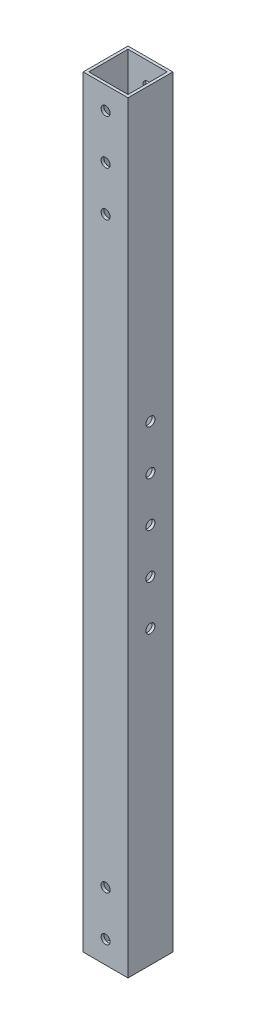
SolidWorks part; units mm, degrees
material "6061-T6 (SS)"
ref_plane "Front Plane" through (0, 0, 0) normal (0, 0, 1) x (1, 0, 0)
ref_plane "Top Plane" through (0, 0, 0) normal (0, 1, 0) x (1, 0, 0)
ref_plane "Right Plane" through (0, 0, 0) normal (1, 0, 0) x (0, 0, -1)
sketch "Sketch1" plane through (0, 0, 0) normal (0, 1, 0) x (1, 0, 0)
  line L1 (-12.7, -12.7) -> (12.7, -12.7)
  line L2 (-12.7, -12.7) -> (-12.7, 12.7)
  line L3 (-12.7, 12.7) -> (12.7, 12.7)
  line L4 (12.7, -12.7) -> (12.7, 12.7)
  line L5 (-12.7, -12.7) -> (12.7, 12.7) construction
  line L6 (-12.7, 12.7) -> (12.7, -12.7) construction
  line L7 (-11.1125, -11.1125) -> (11.1125, -11.1125)
  line L8 (-11.1125, -11.1125) -> (-11.1125, 11.1125)
  line L9 (-11.1125, 11.1125) -> (11.1125, 11.1125)
  line L10 (11.1125, -11.1125) -> (11.1125, 11.1125)
  line L11 (-11.1125, -11.1125) -> (11.1125, 11.1125) construction
  line L12 (-11.1125, 11.1125) -> (11.1125, -11.1125) construction
  point P0 (0, 0)
  point P6 (0, 0)
  dimension "D1" = 25.4
  dimension "D2" = 1.5875
extrude "Boss-Extrude1" add sketch "Sketch1" along normal blind 431.8
hole_wizard "#7 (0.201) Diameter Hole1" positions "Sketch2" profile "Sketch3" hole size "#7" standard "ANSI Inch"
sketch "Sketch2" plane through (0, 0, 12.7) normal (0, 0, 1) x (1, 0, 0)
  line L0 (-12.7, 0) -> (12.7, 0) construction
  point P0 (0, 12.7)
  point P12 (0, 38.1)
  point P25 (0, 368.3)
  point P26 (0, 393.7)
  point P27 (0, 419.1)
  point P30 (0, 342.9) [skipped]
  point P31 (0, 317.5) [skipped]
  point P32 (0, 292.1) [skipped]
  point P33 (0, 266.7) [skipped]
  point P34 (0, 241.3) [skipped]
  point P35 (0, 215.9) [skipped]
  point P36 (0, 190.5) [skipped]
  point P37 (0, 165.1) [skipped]
  point P38 (0, 139.7) [skipped]
  point P39 (0, 114.3) [skipped]
  point P40 (0, 88.9) [skipped]
  point P41 (0, 63.5) [skipped]
  dimension "D1" = 12.7
  dimension "D3" = 25.4
  dimension "D2" = 17
sketch "Sketch3" plane through (0, 12.7, 12.7) normal (1, 0, 0) x (0, -1, 0)
  line L0 (0, 0) -> (0, 25.4)
  line L1 (0, 25.4) -> (2.5527, 25.4)
  line L2 (2.5527, 25.4) -> (2.5527, 0)
  line L5 (2.5527, 0) -> (0, 0)
  line L11 (0, -6.35) -> (0, 107.95) construction
  dimension "Thru Hole Dia." = 5.1054
  dimension "Thru Hole Depth" = 25.4
hole_wizard "#7 (0.201) Diameter Hole2" positions "Sketch4" profile "Sketch5" hole size "#7" standard "ANSI Inch"
sketch "Sketch4" plane through (12.7, 0, 0) normal (1, 0, 0) x (0, 0, -1)
  line L1 (-12.7, 0) -> (12.7, 0) construction
  point P17 (0, 165.1)
  point P18 (0, 190.5)
  point P19 (0, 215.9)
  point P20 (0, 241.3)
  point P21 (0, 266.7)
  point P29 (0, 419.1)
  point P30 (0, 393.7)
  point P31 (0, 368.3)
  point P32 (0, 342.9)
  point P33 (0, 317.5)
  point P34 (0, 292.1)
  point P35 (0, 139.7)
  point P36 (0, 114.3)
  point P37 (0, 88.9)
  point P38 (0, 63.5)
  point P39 (0, 38.1)
  dimension "D1" = 165.1
  dimension "D3" = 25.4
  dimension "D2" = 25.4
  dimension "D4" = 25.4
  dimension "D5" = 25.4
sketch "Sketch5" plane through (12.7, 165.1, 0) normal (0, 1, 0) x (0, 0, -1)
  line L0 (0, 0) -> (0, 25.4)
  line L1 (0, 25.4) -> (2.5527, 25.4)
  line L2 (2.5527, 25.4) -> (2.5527, 0)
  line L5 (2.5527, 0) -> (0, 0)
  line L11 (0, -6.35) -> (0, 107.95) construction
  dimension "Thru Hole Dia." = 5.1054
  dimension "Thru Hole Depth" = 25.4
